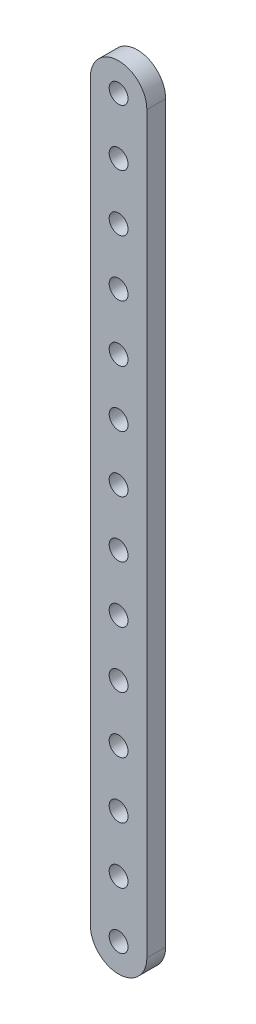
SolidWorks part; units mm, degrees
ref_plane "Alzado" through (0, 0, 0) normal (0, 0, 1) x (1, 0, 0)
ref_plane "Planta" through (0, 0, 0) normal (0, 1, 0) x (1, 0, 0)
ref_plane "Vista lateral" through (0, 0, 0) normal (1, 0, 0) x (0, 0, -1)
sketch "Model" plane through (0, 0, 0) normal (0, 0, 1) x (1, 0, 0)
  line L0 (213.2508, 71.4285) -> (213.2508, 188.4285)
  line L1 (204.2508, 188.4285) -> (204.2508, 71.4285)
  circle A0 centre (208.7508, 179.4285) radius 1.5
  circle A1 centre (208.7508, 188.4285) radius 1.5
  circle A2 centre (208.7508, 152.4285) radius 1.5
  circle A3 centre (208.7508, 161.4285) radius 1.5
  circle A4 centre (208.7508, 170.4285) radius 1.5
  arc A5 (204.2508, 71.4285) -> (213.2508, 71.4285) centre (208.7508, 71.4285) ccw
  arc A6 (213.2508, 188.4285) -> (204.2508, 188.4285) centre (208.7508, 188.4285) ccw
  circle A7 centre (208.7508, 143.4285) radius 1.5
  circle A8 centre (208.7508, 116.4285) radius 1.5
  circle A9 centre (208.7508, 125.4285) radius 1.5
  circle A10 centre (208.7508, 134.4285) radius 1.5
  circle A11 centre (208.7508, 71.4285) radius 1.5
  circle A12 centre (208.7508, 80.4285) radius 1.5
  circle A13 centre (208.7508, 89.4285) radius 1.5
  circle A14 centre (208.7508, 98.4285) radius 1.5
  circle A15 centre (208.7508, 107.4285) radius 1.5
extrude "Saliente-Extruir1" add sketch "Model" along normal blind 3
